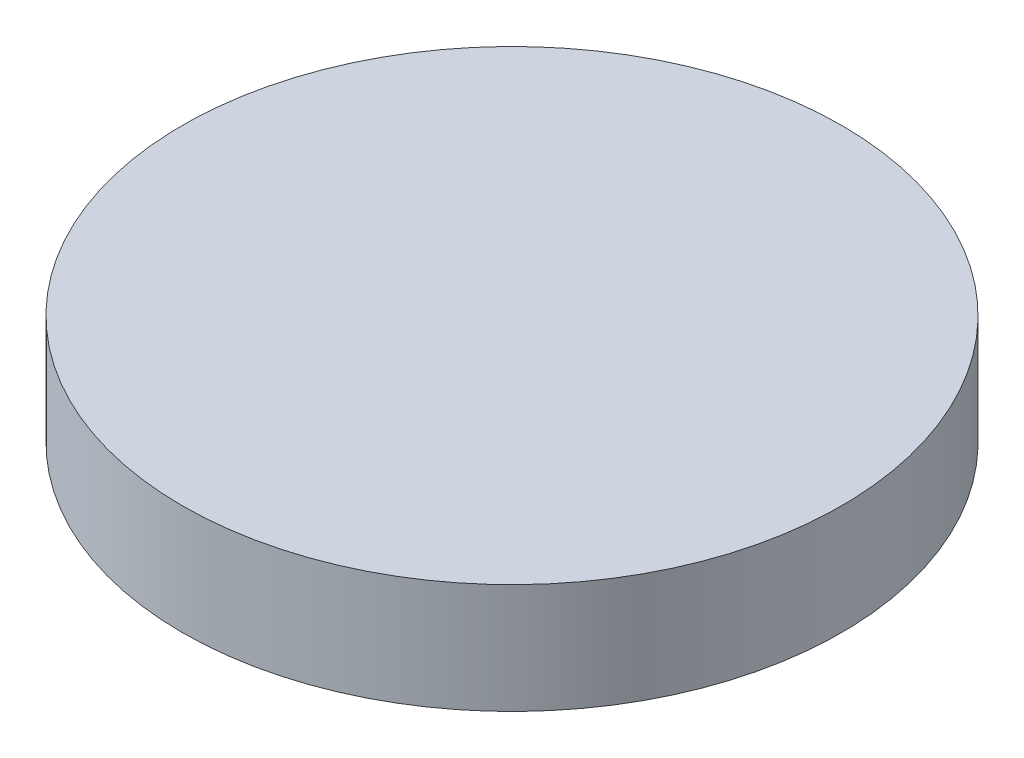
SolidWorks part; units mm, degrees
ref_plane "Front Plane" through (0, 0, 0) normal (0, 0, 1) x (1, 0, 0)
ref_plane "Top Plane" through (0, 0, 0) normal (0, 1, 0) x (1, 0, 0)
ref_plane "Right Plane" through (0, 0, 0) normal (1, 0, 0) x (0, 0, -1)
sketch "Sketch1" plane through (0, 0, 0) normal (0, 1, 0) x (1, 0, 0)
  circle A0 centre (0, 0) radius 3
  dimension "D1" = 6
extrude "Boss-Extrude1" add sketch "Sketch1" along normal blind 1
